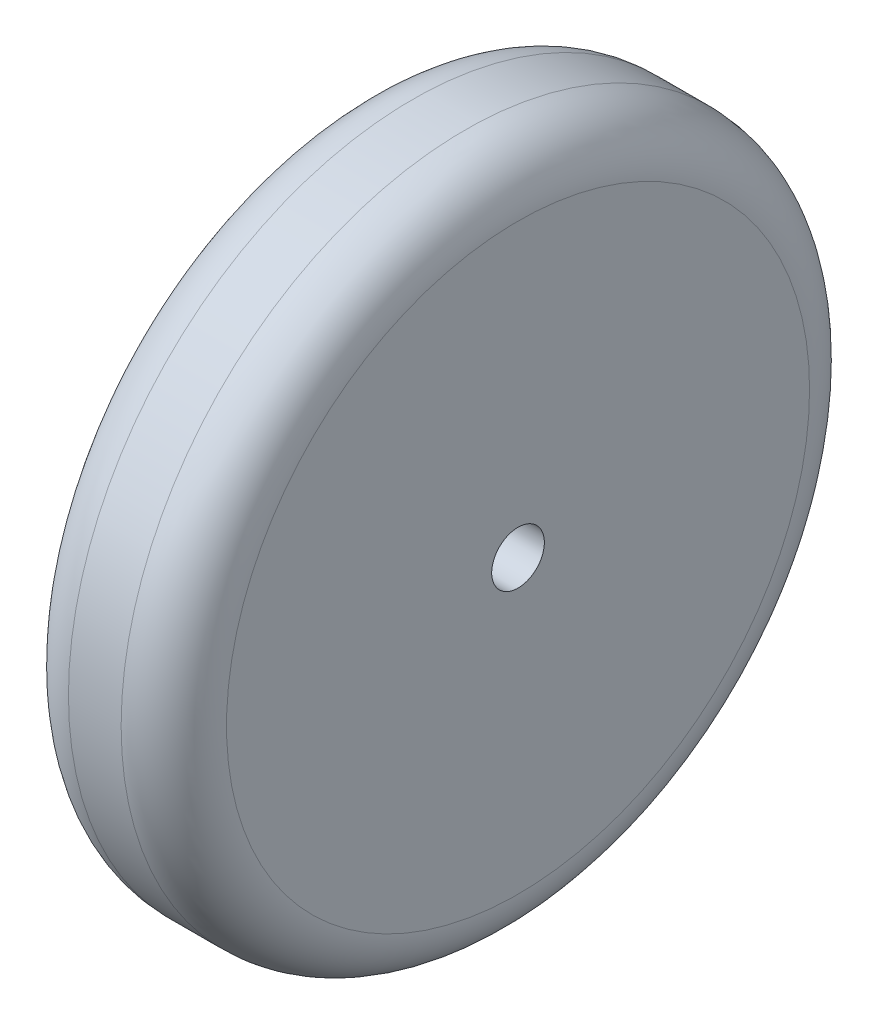
SolidWorks part; units mm, degrees
material "Rubber"
ref_plane "Front Plane" through (0, 0, 0) normal (0, 0, 1) x (1, 0, 0)
ref_plane "Top Plane" through (0, 0, 0) normal (0, 1, 0) x (1, 0, 0)
ref_plane "Right Plane" through (0, 0, 0) normal (1, 0, 0) x (0, 0, -1)
sketch "Sketch1" plane through (0, 0, 0) normal (1, 0, 0) x (0, 0, -1)
  circle A0 centre (0, 0) radius 5
  circle A1 centre (0, 0) radius 65.3277
  dimension "D1" = 10
extrude "Boss-Extrude1" add sketch "Sketch1" along normal blind 30
fillet "Fillet1" radius 10 2 edges at (30, 0, -65.3277) (0, 0, -65.3277)
